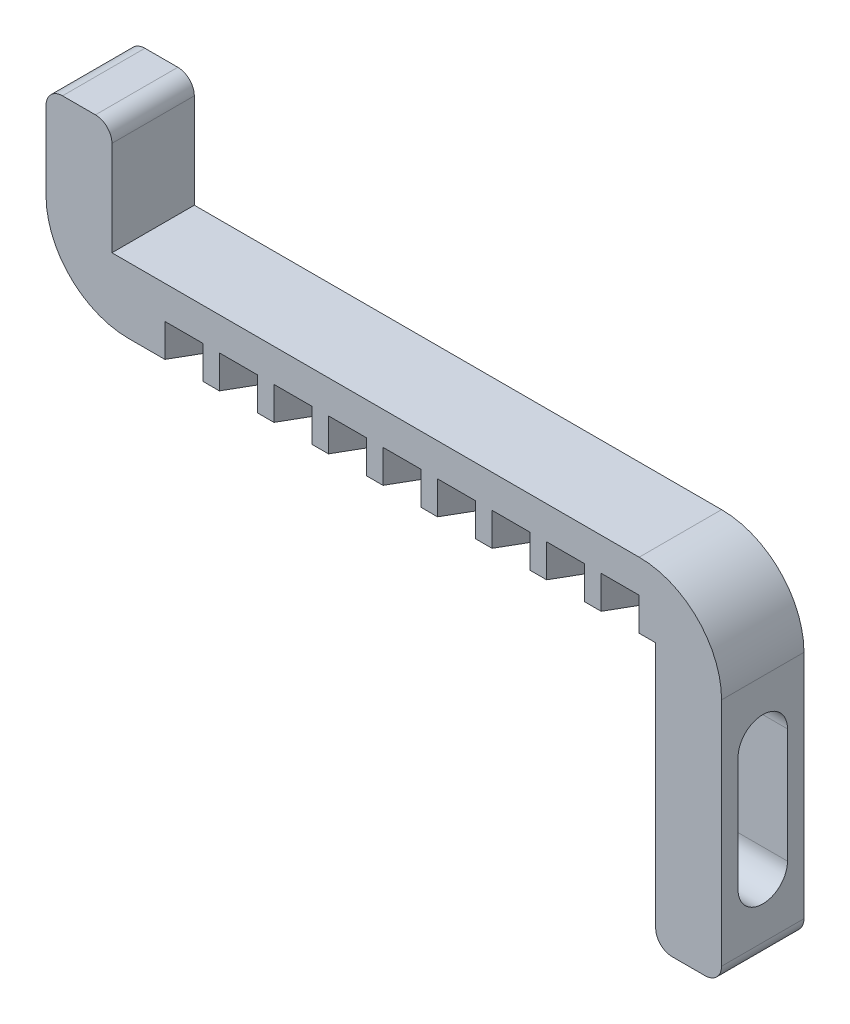
SolidWorks part; units mm, degrees
ref_plane "Front Plane" through (0, 0, 0) normal (0, 0, 1) x (1, 0, 0)
ref_plane "Top Plane" through (0, 0, 0) normal (0, 1, 0) x (1, 0, 0)
ref_plane "Right Plane" through (0, 0, 0) normal (1, 0, 0) x (0, 0, -1)
sketch "Sketch1" plane through (0, 0, 0) normal (0, 0, 1) x (1, 0, 0)
  line L1 (0, 0) -> (33, 0)
  line L3 (0, 4) -> (37, 4)
  line L5 (0, 0) -> (-4, 0)
  line L6 (0, 4) -> (0, 10.75)
  line L7 (0, 10.75) -> (-4, 10.75)
  line L8 (-4, 0) -> (-4, 10.75)
  line L9 (37, 4) -> (33, 4)
  line L10 (37, 4) -> (37, -16)
  line L11 (37, -16) -> (33, -16)
  line L12 (33, 0) -> (33, -16)
  dimension "D1" = 37
  dimension "D2" = 20
  dimension "D3" = 4
  dimension "D4" = 4
  dimension "D5" = 6.75
  dimension "D6" = 4
extrude "Boss-Extrude1" add sketch "Sketch1" along normal blind 5 contours L1 L12 L11 L10 L3 L6 L7 L8 L5
ref_plane "Plane2" through (33, 0, 0) normal (-1, 0, 0) x (0, 0, 1)
sketch "Sketch3" plane through (33, 0, 0) normal (-1, 0, 0) x (0, 0, 1)
  line L0 (2.5, -4.5241) -> (2.5, -11.4759) construction
  line L1 (4, -4.5241) -> (4, -11.4759)
  line L2 (1, -4.5241) -> (1, -11.4759)
  line L3 (5, -16) -> (0, -16) construction
  line L4 (0, 0) -> (0, -16) construction
  arc A0 (4, -4.5241) -> (1, -4.5241) centre (2.5, -4.5241) ccw
  arc A1 (1, -11.4759) -> (4, -11.4759) centre (2.5, -11.4759) ccw
  point P2 (2.5, -8)
  dimension "D1" = 8
  dimension "D2" = 3
  dimension "D3" = 2.5
extrude "Cut-Extrude1" cut sketch "Sketch3" against normal through all
fillet "Fillet2" radius 5 2 edges at (37, 4, 2.5) (-4, 0, 2.5)
fillet "Fillet3" radius 1 4 edges at (37, -16, 2.5) (33, -16, 2.5) (0, 10.75, 2.5) (-4, 10.75, 2.5)
ref_plane "Plane3" through (0, 0, 0) normal (0, -1, 0) x (-1, 0, 0)
sketch "Sketch4" plane through (0, 0, 0) normal (0, -1, 0) x (-1, 0, 0)
  line L0 (-2, -5) -> (-2, 0.7051) construction
  line L1 (-1, -5) -> (-33, -5) construction
  line L2 (-1, -5) -> (-1, 0) construction
  line L3 (-1, 0) -> (-33, 0) construction
  line L4 (-30.8453, -3) -> (-32, -5)
  line L5 (-32, -5) -> (-29.6906, -5)
  line L6 (-29.6906, -5) -> (-30.8453, -3)
  line L7 (-30.8453, -2) -> (-29.6906, 0)
  line L8 (-29.6906, 0) -> (-32, 0)
  line L9 (-27.5353, -3) -> (-28.69, -5)
  line L11 (-32, 0) -> (-30.8453, -2)
  line L12 (-28.69, -5) -> (-26.3806, -5)
  line L13 (-26.3806, -5) -> (-27.5353, -3)
  line L14 (-27.5353, -2) -> (-26.3806, 0)
  line L15 (-26.3806, 0) -> (-28.69, 0)
  line L16 (-28.69, 0) -> (-27.5353, -2)
  line L17 (-24.2253, -3) -> (-25.38, -5)
  line L18 (-25.38, -5) -> (-23.0706, -5)
  line L19 (-23.0706, -5) -> (-24.2253, -3)
  line L20 (-24.2253, -2) -> (-23.0706, 0)
  line L21 (-23.0706, 0) -> (-25.38, 0)
  line L22 (-25.38, 0) -> (-24.2253, -2)
  line L23 (-20.9153, -3) -> (-22.07, -5)
  line L24 (-22.07, -5) -> (-19.7606, -5)
  line L25 (-19.7606, -5) -> (-20.9153, -3)
  line L26 (-20.9153, -2) -> (-19.7606, 0)
  line L27 (-19.7606, 0) -> (-22.07, 0)
  line L28 (-22.07, 0) -> (-20.9153, -2)
  line L29 (-17.6053, -3) -> (-18.76, -5)
  line L30 (-18.76, -5) -> (-16.4506, -5)
  line L31 (-16.4506, -5) -> (-17.6053, -3)
  line L32 (-17.6053, -2) -> (-16.4506, 0)
  line L33 (-16.4506, 0) -> (-18.76, 0)
  line L34 (-18.76, 0) -> (-17.6053, -2)
  line L35 (-14.2953, -3) -> (-15.45, -5)
  line L36 (-15.45, -5) -> (-13.1406, -5)
  line L37 (-13.1406, -5) -> (-14.2953, -3)
  line L38 (-14.2953, -2) -> (-13.1406, 0)
  line L39 (-13.1406, 0) -> (-15.45, 0)
  line L40 (-15.45, 0) -> (-14.2953, -2)
  line L41 (-10.9853, -3) -> (-12.14, -5)
  line L42 (-12.14, -5) -> (-9.8306, -5)
  line L43 (-9.8306, -5) -> (-10.9853, -3)
  line L44 (-10.9853, -2) -> (-9.8306, 0)
  line L45 (-9.8306, 0) -> (-12.14, 0)
  line L46 (-12.14, 0) -> (-10.9853, -2)
  line L47 (-7.6753, -3) -> (-8.83, -5)
  line L48 (-8.83, -5) -> (-6.5206, -5)
  line L49 (-6.5206, -5) -> (-7.6753, -3)
  line L50 (-7.6753, -2) -> (-6.5206, 0)
  line L51 (-6.5206, 0) -> (-8.83, 0)
  line L52 (-8.83, 0) -> (-7.6753, -2)
  line L53 (-4.3653, -3) -> (-5.52, -5)
  line L54 (-5.52, -5) -> (-3.2106, -5)
  line L55 (-3.2106, -5) -> (-4.3653, -3)
  line L56 (-4.3653, -2) -> (-3.2106, 0)
  line L57 (-3.2106, 0) -> (-5.52, 0)
  line L58 (-5.52, 0) -> (-4.3653, -2)
  line L59 (-30.8453, -3) -> (-27.5353, -3) construction
  circle A0 centre (-30.8453, -4.3333) radius 1.3333 construction
  circle A1 centre (-30.8453, -0.6667) radius 0.6667 construction
  circle A2 centre (-27.5353, -4.3333) radius 1.3333 construction
  circle A3 centre (-27.5353, -0.6667) radius 0.6667 construction
  circle A4 centre (-24.2253, -4.3333) radius 1.3333 construction
  circle A5 centre (-24.2253, -0.6667) radius 0.6667 construction
  circle A6 centre (-20.9153, -4.3333) radius 1.3333 construction
  circle A7 centre (-20.9153, -0.6667) radius 0.6667 construction
  circle A8 centre (-17.6053, -4.3333) radius 1.3333 construction
  circle A9 centre (-17.6053, -0.6667) radius 0.6667 construction
  circle A10 centre (-14.2953, -4.3333) radius 1.3333 construction
  circle A11 centre (-14.2953, -0.6667) radius 0.6667 construction
  circle A12 centre (-10.9853, -4.3333) radius 1.3333 construction
  circle A13 centre (-10.9853, -0.6667) radius 0.6667 construction
  circle A14 centre (-7.6753, -4.3333) radius 1.3333 construction
  circle A15 centre (-7.6753, -0.6667) radius 0.6667 construction
  circle A16 centre (-4.3653, -4.3333) radius 1.3333 construction
  circle A17 centre (-4.3653, -0.6667) radius 0.6667 construction
  dimension "D1" = 1
  dimension "D2" = 2
  dimension "D3" = 0
  dimension "D4" = 2
  dimension "D5" = 0
  dimension "D6" = 9
  dimension "D7" = 3.31
extrude "Cut-Extrude2" cut sketch "Sketch4" against normal blind 2
